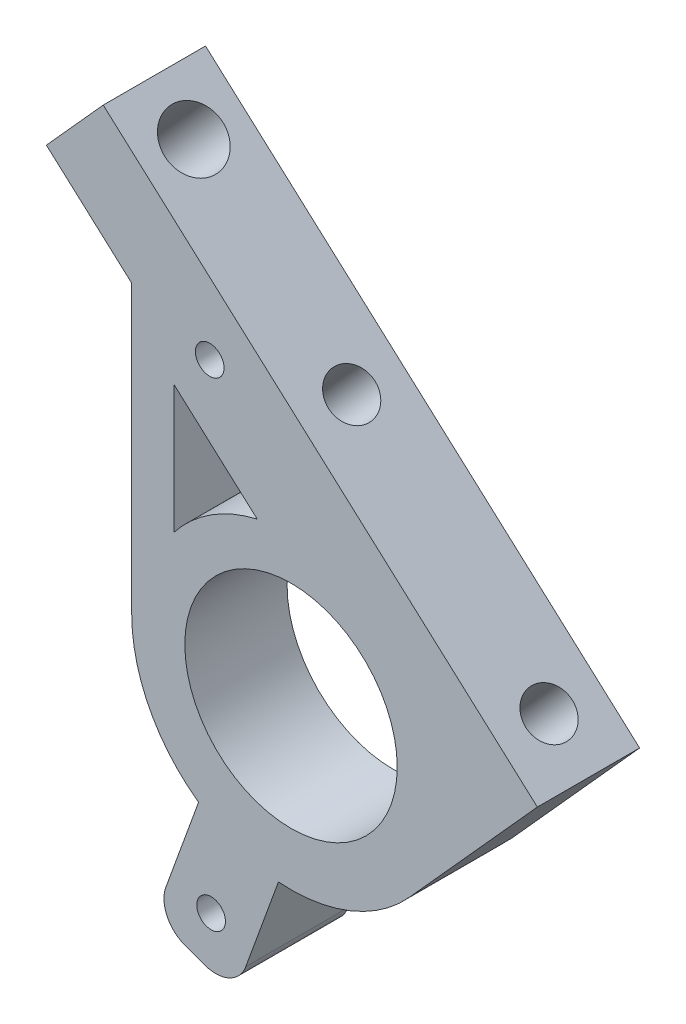
SolidWorks part; units mm, degrees
material "6061 Alloy"
ref_plane "Front Plane" through (0, 0, 0) normal (0, 0, 1) x (1, 0, 0)
ref_plane "Top Plane" through (0, 0, 0) normal (0, 1, 0) x (1, 0, 0)
ref_plane "Right Plane" through (0, 0, 0) normal (1, 0, 0) x (0, 0, -1)
sketch "Sketch1" plane through (0, 0, 0) normal (0, 0, 1) x (1, 0, 0)
  line L0 (-17.6814, 40.1418) -> (21.9261, 40.1418) construction
  line L1 (-15, 0) -> (-15, 26.9624)
  line L2 (-15, 26.9624) -> (-23.0345, 34.1967)
  line L3 (-23.0345, 34.1967) -> (-17.6814, 40.1418)
  line L4 (-17.6814, 40.1418) -> (23.1915, 3.3396)
  line L5 (23.1915, 3.3396) -> (17.8385, -2.6055)
  line L10 (17.8385, -2.6055) -> (11.1472, -10.037)
  line L11 (-15, 26.9624) -> (17.8385, -2.6055) construction
  circle A0 centre (0, 0) radius 10
  arc A1 (-15, 0) -> (11.1472, -10.037) centre (0, 0) ccw
  dimension "D3" = 20
  dimension "D4" = 5
  dimension "D1" = 42
  dimension "D2" = 8
  dimension "D7" = 55
extrude "3/8" add sketch "Sketch1" along normal blind 9.63
sketch "Sketch2" plane through (0, 0, 0) normal (0, 0, 1) x (1, 0, 0)
  line L0 (0, 0) -> (0, -7.8768) construction
  line L1 (-8.7033, -12.2169) -> (-1.1858, -14.9531)
  line L2 (-8.7033, -12.2169) -> (-12.8075, -23.4932)
  line L3 (-12.8075, -23.4932) -> (-5.29, -26.2294)
  line L4 (-1.1858, -14.9531) -> (-5.29, -26.2294)
  line L5 (-9.0488, -24.8613) -> (-4.9445, -13.585) construction
  line L6 (-10.7554, -17.8551) -> (-3.2379, -20.5912) construction
  arc A0 (-15, 0) -> (11.1472, -10.037) centre (0, 0) ccw construction
  point P360 (-6.9966, -19.2231)
  dimension "D1" = 12
  dimension "D2" = 8
  dimension "D3" = 110
extrude "Boss-Extrude2" add sketch "Sketch2" along normal up to surface (9.63 mm away) up to face at (-6.6377, 14.2697, 9.63)
sketch "Sketch3" plane through (0, 0, 9.63) normal (0, 0, 1) x (1, 0, 0)
  line L0 (0, 0) -> (-9.0488, -24.8613) construction
  line L1 (-12.8075, -23.4932) -> (-5.29, -26.2294) construction
  circle A0 centre (-7.5244, -20.6732) radius 1.35
  dimension "D2" = 2.7
  dimension "D1" = 22
extrude "M3_DRILL_or_Through" cut sketch "Sketch3" against normal up to surface (9.63 mm away) up to face at (-6.5272, 1.5509, 0)
fillet "Fillet1" radius 3 2 edges at (-5.29, -26.2294, 4.815) (-12.8075, -23.4932, 4.815)
sketch "Sketch4" plane through (12.0444, 13.3766, 0) normal (0.6691, 0.7431, 0) x (0.7431, -0.6691, 0)
  line L0 (-40, -4.815) -> (15, -4.815) construction
  line L1 (-40, -9.63) -> (-40, 0) construction
  line L2 (15, -9.63) -> (15, 0) construction
  circle A0 centre (-35, -4.815) radius 2.75
  dimension "D2" = 5.5
  dimension "D1" = 5
extrude "M5_through" cut sketch "Sketch4" against normal up to surface (8 mm away) up to face at (-19.0172, 30.5795, 4.815)
sketch "Sketch5" plane through (12.0444, 13.3766, 0) normal (0.6691, 0.7431, 0) x (0.7431, -0.6691, 0)
  line L0 (-35, -4.815) -> (10, -4.815) construction
  circle A0 centre (-15, -4.815) radius 2.2
  circle A1 centre (10, -4.815) radius 2.2
  dimension "D1" = 4.4
  dimension "D2" = 20
  dimension "D3" = 45
extrude "M5_DRILL" cut sketch "Sketch5" against normal blind 8
sketch "Sketch6" plane through (0, 0, 9.63) normal (0, 0, 1) x (1, 0, 0)
  line L0 (-11, 20.6695) -> (-11, 8.6603)
  line L1 (-11, 20.6695) -> (-3.185, 13.6329)
  line L2 (23.1915, 3.3396) -> (-17.6814, 40.1418) construction
  line L3 (-15, 26.9624) -> (-15, 0) construction
  arc A0 (-11, 8.6603) -> (-3.185, 13.6329) centre (0, 0) cw
  circle A1 centre (0, 0) radius 10 construction
  dimension "D3" = 4
  dimension "D1" = 10
  dimension "D2" = 4
extrude "Cut-Extrude4" cut sketch "Sketch6" against normal up to vertex (9.63 mm away)
sketch "Sketch7" plane through (0, 0, 9.63) normal (0, 0, 1) x (1, 0, 0)
  line L0 (-11, 20.6695) -> (-4.3087, 28.101) construction
  line L1 (23.1915, 3.3396) -> (-17.6814, 40.1418) construction
  circle A0 centre (-7.6543, 24.3852) radius 1.35
  dimension "D1" = 2.7
extrude "M3_DRILL_or_Through2" cut sketch "Sketch7" against normal up to surface (9.63 mm away) up to face at (-8.5361, 14.5426, 0)
